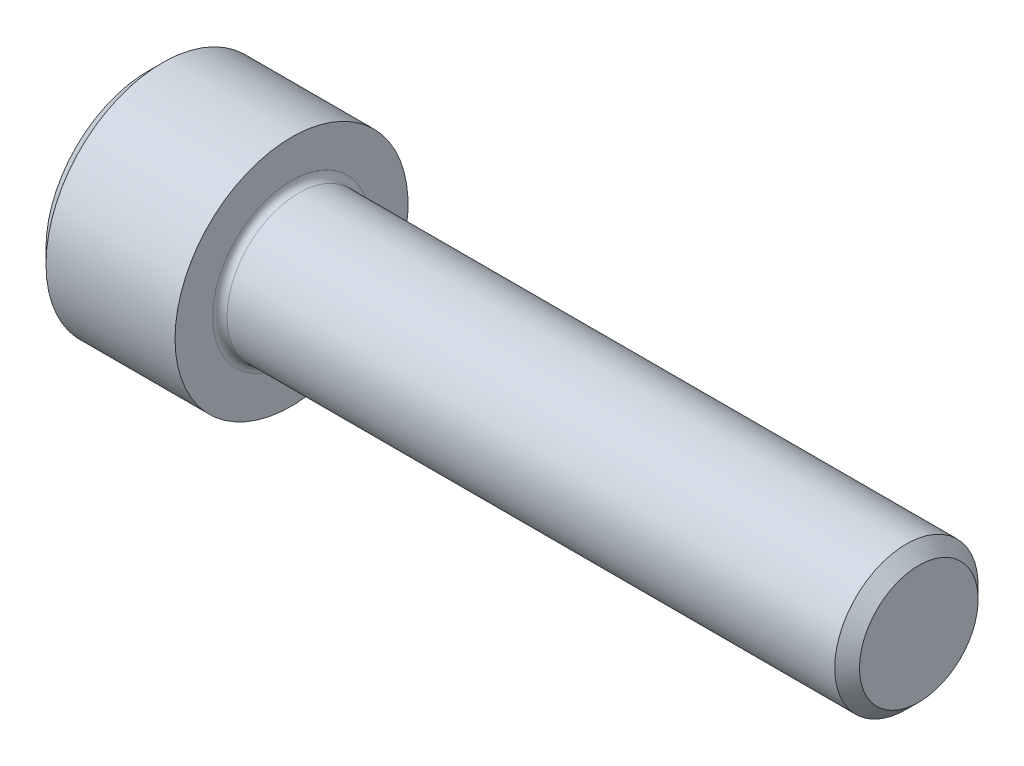
SolidWorks part; units mm, degrees
revolve "Base-Revolve" add sketch "BodySke"
sketch "BodySke" plane through (0, 0, 0) normal (0, 0, 1) x (1, 0, 0)
  line L0 (0, 0) -> (0, 5.7)
  line L1 (0.8, 6.5) -> (8, 6.5)
  line L2 (8, 6.5) -> (8, 4)
  line L3 (8, 4) -> (42.3095, 4)
  line L4 (43, 3.3095) -> (43, 0)
  line L5 (43, 0) -> (0, 0)
  line L6 (-31.75, 0) -> (127, 0) construction
  line L7 (0, 5.7) -> (0.8, 6.5)
  line L8 (43, 3.3095) -> (42.3095, 4)
  line L9 (0, -5.7) -> (0.8, -6.5) construction
  line L10 (43, -3.3095) -> (42.3095, -4) construction
  line L11 (9.25, 2.4825) -> (9.25, -3.8675) construction
  line L12 (8, 2.4825) -> (8, -3.8675) construction
  line L13 (-7, 2.4825) -> (-7, -3.8675) construction
  dimension "Diameter" = 8
  dimension "Head_ht" = 8
  dimension "Length" = 35
  dimension "Body_ch_ang" = 45
  dimension "Head_dia" = 13
  dimension "Head_ch_ang" = 45
  dimension "Minor_dia" = 6.619
  dimension "Advance" = 1.25
  dimension "Thread_nom" = 35
  dimension "Thread_length" = 50
  dimension "Head_ch_ht" = 0.8
cosmetic thread "ThreadCosmetic"
fillet "Fillet1" radius 0.4 1 edges at (8, 0, 4)
ref_plane "Plane1" through (0, 0, 0) normal (0, 0, 1) x (1, 0, 0)
ref_plane "Plane2" through (0, 0, 0) normal (0, 1, 0) x (1, 0, 0)
ref_plane "Plane3" through (0, 0, 0) normal (1, 0, 0) x (0, 0, -1)
other "Configuration Table"
sketch "Sketch2" plane through (0, 0, 0) normal (0, 0, 1) x (1, 0, 0)
  line L0 (0, 3.0475) -> (4, 3.0475)
  line L1 (4, 3.0475) -> (5.7595, 0)
  line L2 (-31.75, 0) -> (127, 0) construction
  line L3 (5.7595, 0) -> (0, 0)
  line L4 (0, 0) -> (0, 3.0475)
  line L5 (0, 5.7) -> (0, -5.7) construction
  line L6 (0, 0) -> (47.625, 0) construction
  line L7 (8, -6.5) -> (8, 6.5) construction
  dimension "D1" = 3.0475
  dimension "D2" = 60
revolve "Hex-PreBroach" cut sketch "Sketch2" angle 360 about L6
sketch "Sketch3" plane through (0, 0, 0) normal (-1, 0, 0) x (0, 0.5, 0.866)
  line L0 (1.7595, 3.0475) -> (-1.7595, 3.0475)
  line L1 (-1.7595, 3.0475) -> (-3.5189, 0)
  line L2 (1.7595, 3.0475) -> (3.5189, 0)
  line L3 (1.7595, -3.0475) -> (3.5189, 0)
  line L4 (1.7595, -3.0475) -> (-1.7595, -3.0475)
  line L5 (-1.7595, -3.0475) -> (-3.5189, 0)
  dimension "D1" = 3.0475
  dimension "D2" = 3.0475
  dimension "Hex_size" = 6.095
extrude "Hex" cut sketch "Sketch3" against normal blind 4
sketch "Sketch4" plane through (0, 0, 0) normal (-1, 0, 0) x (0, 0, 1)
  line L0 (0, 0) -> (3.7846, 0)
  line L1 (0, 0) -> (6.1484, 3.5498) construction
  line L2 (0, 0) -> (1.8923, 3.2776)
  line L3 (3.1235, 0.8061) -> (3.6229, 1.0945)
  line L4 (2.2599, 2.3019) -> (2.7593, 2.5903)
  arc A0 (3.1235, 0.8061) -> (2.2599, 2.3019) centre (0, 0) ccw
  arc A1 (3.7846, 0) -> (3.6229, 1.0945) centre (0, 0) ccw
  arc A2 (1.8923, 3.2776) -> (2.7593, 2.5903) centre (0, 0) cw
  dimension "D1" = 30
  dimension "D2" = 60
  dimension "Spline_p_dim" = 1.7272
  dimension "D3" = 0.8636
extrude "Spline" [suppressed] cut sketch "Sketch4" against normal blind 4
pattern_circular "CirPattern1" [suppressed] count 6 every 60
sketch "Sketch5" plane through (0, 0, 0) normal (0, 0, 1) x (1, 0, 0)
  line L0 (-31.75, 0) -> (127, 0) construction
  line L2 (0, 5.7) -> (0, -5.7) construction
  circle A0 centre (2.7, 0) radius 0.675
  dimension "Drilled_hole_dia" = 1.35
  dimension "Drilled_hole_loc" = 2.7
extrude "Hole" [suppressed] cut sketch "Sketch5" against normal through all and the other way through all
pattern_circular "Drilled-4" [suppressed] count 2 every 60
pattern_circular "Drilled-6" [suppressed] count 3 every 60
sketch "ThdSchSke" plane through (0, 0, 0) normal (0, 0, 1) x (1, 0, 0)
  line L0 (9.25, -3.3095) -> (8.7665, -4)
  line L1 (9.25, -3.3095) -> (9.7335, -4)
  line L2 (9.7335, -4) -> (9.7335, -5)
  line L3 (-3.175, 0) -> (5.1513, 0) construction
  line L5 (9.7335, -5) -> (8.7665, -5)
  line L6 (8.7665, -5) -> (8.7665, -4)
  line L7 (0, 5.7) -> (0, -5.7) construction
  dimension "Thread_minor" = 6.619
  dimension "Diameter" = 8
  dimension "Start" = 9.25
revolve "ThreadSchematic" [suppressed] cut sketch "ThdSchSke" angle 360 about L3
pattern_linear "ThdSchPat" [suppressed]
equation "\"D2@Sketch3\" = \"Hex_size@Sketch3\" / 2"
equation "\"D1@Sketch3\" = \"Hex_size@Sketch3\" / 2"
equation "\"D1@Sketch2\" = \"Hex_size@Sketch3\" / 2"
equation "\"D3@Sketch4\" = \"Spline_p_dim@Sketch4\" / 2"
equation "\"Thread_minor@ThreadCosmetic\"  =  \"Minor_dia@BodySke\""
equation "\"D2@CirPattern1\" = 360 / \"Num_teeth@CirPattern1\""
equation "\"Wall_thickness@Sketch2\" = \"Head_ht@BodySke\" - \"Key_eng@Hex\""
equation "\"Thread_length@ThreadCosmetic\" = ((sgn( (\"Length@BodySke\" - \"Advance@BodySke\" ) - \"Thread_nom@BodySke\" )-1)*( (\"Length@BodySke\" - \"Advance@BodySke\" ) - \"Thread_nom@BodySke\" ))/-2+ \"Thread_nom@BodySke\""
equation "\"Thread_minor@ThdSchSke\" = \"Minor_dia@BodySke\""
equation "\"Diameter@ThdSchSke\" = \"Diameter@BodySke\""
equation "\"Overcut@ThdSchSke\" = \"Diameter@BodySke\" * 1.25"
equation "\"Start@ThdSchSke\" = \"Head_ht@BodySke\" + \"Length@BodySke\" - \"Thread_length@ThreadCosmetic\"  '---Non-countersunk---"
equation "\"Num_threads@ThdSchPat\" = int( \"Thread_length@ThreadCosmetic\" / \"Advance@BodySke\" + 0.999 )  + 1"
equation "\"Advance@ThdSchPat\" = \"Thread_length@ThreadCosmetic\" /  (\"Num_threads@ThdSchPat\" - 1) 'relax it"
equation "\"Num_threads@ThdSchPat\" = \"Num_threads@ThdSchPat\" - sgn( \"Num_threads@ThdSchPat\" - 1) '---chamfered tips only---"
